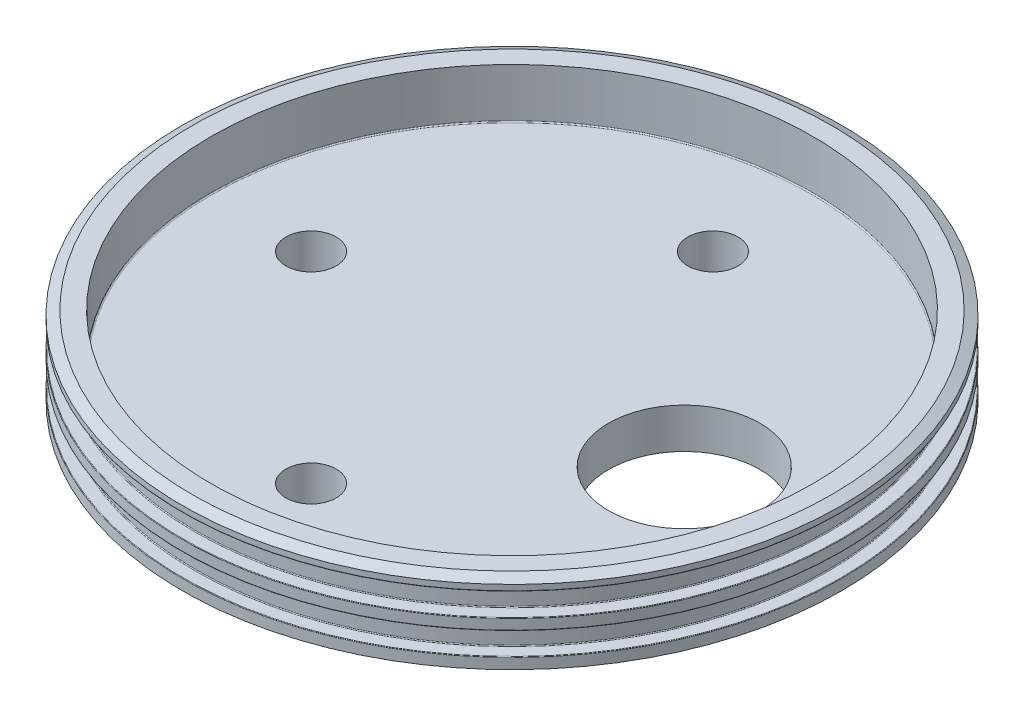
SolidWorks part; units mm, degrees
material "6061-T6 (SS)"
ref_plane "Front Plane" through (0, 0, 0) normal (0, 0, 1) x (1, 0, 0)
ref_plane "Top Plane" through (0, 0, 0) normal (0, 1, 0) x (1, 0, 0)
ref_plane "Right Plane" through (0, 0, 0) normal (1, 0, 0) x (0, 0, -1)
sketch "Sketch1" plane through (0, 0, 0) normal (0, 0, 1) x (1, 0, 0)
  line L0 (0, 48.1922) -> (0, -25.6743) construction
  line L1 (0, 0) -> (72.898, 0)
  line L2 (72.898, 0) -> (72.898, 2.4638)
  line L3 (72.898, 2.4638) -> (69.977, 2.4638)
  line L4 (69.977, 2.4638) -> (69.977, 7.4422)
  line L5 (69.977, 7.4422) -> (72.898, 7.4422)
  line L6 (72.898, 7.4422) -> (72.898, 9.906)
  line L7 (72.898, 9.906) -> (69.977, 9.906)
  line L8 (66.548, 17.3482) -> (66.548, 6.35)
  line L9 (66.548, 6.35) -> (0, 6.35)
  line L10 (0, 6.35) -> (0, 0)
  line L11 (69.977, 9.906) -> (69.977, 14.986)
  line L12 (69.977, 14.986) -> (72.898, 14.986)
  line L13 (72.898, 14.986) -> (72.898, 17.3482)
  line L14 (72.898, 17.3482) -> (66.548, 17.3482)
  dimension "D1" = 145.796
  dimension "D2" = 4.9784
  dimension "D3" = 2.921
  dimension "D4" = 9.906
  dimension "D5" = 6.35
  dimension "D6" = 6.35
  dimension "D7" = 5.08
  dimension "D8" = 9.906
revolve "Revolve1" add sketch "Sketch1" angle 360 about L0
sketch "Sketch6" plane through (0, 0, 0) normal (0, -1, 0) x (1, 0, 0)
  circle A0 centre (0, 0) radius 66.04
  dimension "D1" = 132.08
extrude "Boss-Extrude1" add sketch "Sketch6" along normal blind 2.54
hole_wizard "Pipe Tap Drill for 1/4 Tap - GN2" positions "Sketch2" profile "Sketch3" hole size "1/4" standard "ANSI Inch" end condition through all
sketch "Sketch2" plane through (0, 6.35, 0) normal (0, 1, 0) x (1, 0, 0)
  point P4 (-44.45, 0)
  dimension "D1" = 44.45
sketch "Sketch3" plane through (-44.45, 6.35, 0) normal (1, 0, 0) x (0, 0, 1)
  line L0 (0, 0) -> (0, 8.89)
  line L1 (0, 8.89) -> (5.5626, 8.89)
  line L2 (5.5626, 8.89) -> (5.5626, 0)
  line L5 (5.5626, 0) -> (0, 0)
  line L11 (0, -6.35) -> (0, 107.95) construction
  dimension "Thru Hole Dia." = 11.1252
  dimension "Thru Hole Depth" = 8.89
fillet "CNC ID Fillet" radius 0.1778 5 edges at (-69.977, 7.4422, 0) (-69.977, 2.4638, 0) (-69.977, 14.986, 0) (-69.977, 9.906, 0) (66.04, 0, 0)
fillet "CNC OD Fillet" radius 0.127 5 edges at (-72.898, 7.4422, 0) (-72.898, 2.4638, 0) (66.04, -2.54, 0) (-72.898, 14.986, 0) (-72.898, 9.906, 0)
chamfer "CNC Chamfers" distance 1.016 angle 65 1 edges at (-72.898, 17.3482, 0)
fillet "CNC Bore Fillet" radius 0.254 1 edges at (-66.548, 6.35, 0)
sketch "Sketch7" plane through (0, -2.54, 0) normal (0, -1, 0) x (-1, 0, 0)
  circle A0 centre (-38.1, 0) radius 16.764
  dimension "D1" = 33.528
  dimension "D2" = 38.1
extrude "Cut-Extrude1-Siphon" cut sketch "Sketch7" against normal through all
hole_wizard "Pipe Tap Drill for 1/4 Tap - Relief Valve" positions "Sketch13" profile "Sketch14" hole size "1/4" standard "ANSI Inch" end condition through all
sketch "Sketch13" plane through (0, -2.54, 0) normal (0, -1, 0) x (-1, 0, 0)
  point P4 (0, 44.45)
  point P5 (0, 44.8156)
  point P7 (0, 0)
  dimension "D1" = 44.45
sketch "Sketch14" plane through (0, -2.54, -44.45) normal (1, 0, 0) x (0, 0, -1)
  line L0 (0, 0) -> (0, 19.8882)
  line L1 (0, 19.8882) -> (5.5626, 19.8882)
  line L2 (5.5626, 19.8882) -> (5.5626, 0)
  line L5 (5.5626, 0) -> (0, 0)
  line L11 (0, -6.35) -> (0, 107.95) construction
  dimension "Thru Hole Dia." = 11.1252
  dimension "Thru Hole Depth" = 19.8882
hole_wizard "Pipe Tap Drill for 1/4 Tap - Vent Valve" positions "Sketch15" profile "Sketch16" hole size "1/4" standard "ANSI Inch" end condition through all
sketch "Sketch15" plane through (0, -2.54, 0) normal (0, -1, 0) x (-1, 0, 0)
  point P4 (0, -44.45)
  point P5 (0, -43.8065)
  point P7 (0, 0)
  dimension "D1" = 44.45
sketch "Sketch16" plane through (0, -2.54, 44.45) normal (1, 0, 0) x (0, 0, -1)
  line L0 (0, 0) -> (0, 19.8882)
  line L1 (0, 19.8882) -> (5.5626, 19.8882)
  line L2 (5.5626, 19.8882) -> (5.5626, 0)
  line L5 (5.5626, 0) -> (0, 0)
  line L11 (0, -6.35) -> (0, 107.95) construction
  dimension "Thru Hole Dia." = 11.1252
  dimension "Thru Hole Depth" = 19.8882
